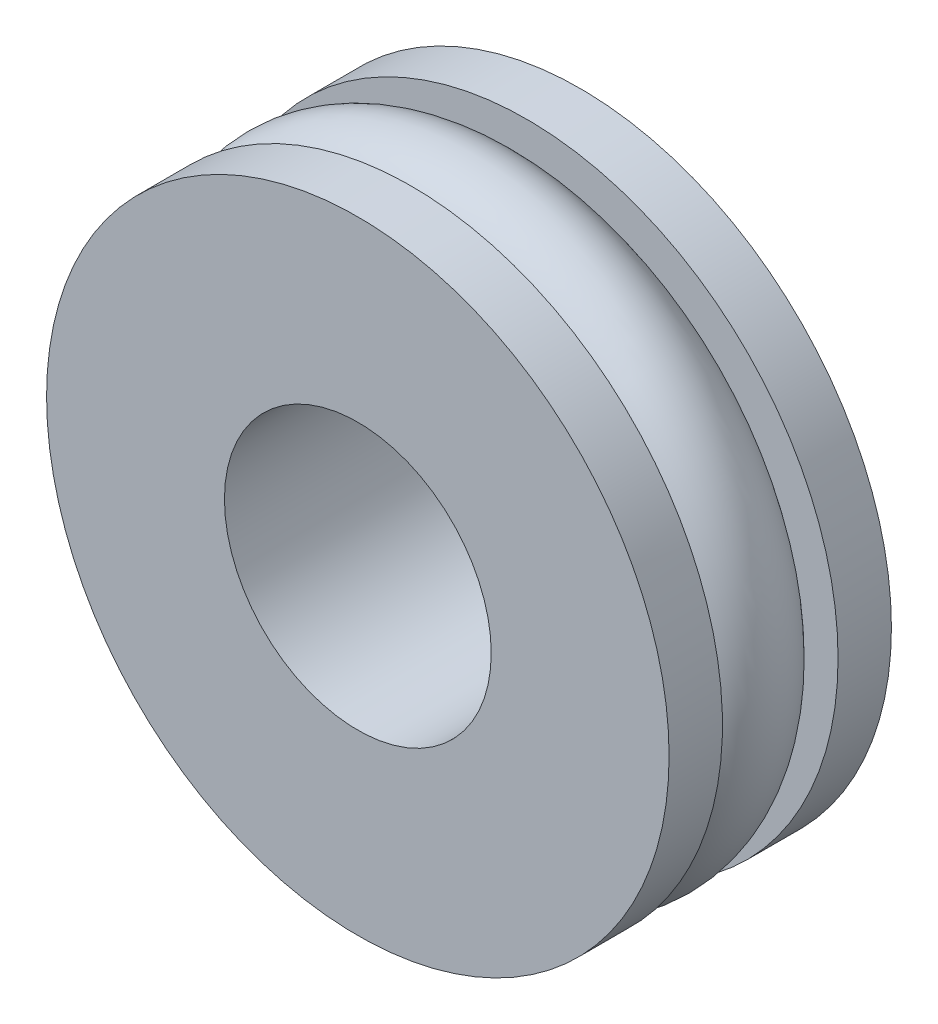
SolidWorks part; units mm, degrees
ref_plane "前视基准面" through (0, 0, 0) normal (0, 0, 1) x (1, 0, 0)
ref_plane "上视基准面" through (0, 0, 0) normal (0, 1, 0) x (1, 0, 0)
ref_plane "右视基准面" through (0, 0, 0) normal (1, 0, 0) x (0, 0, -1)
sketch "草图1" plane through (0, 0, 0) normal (0, 0, 1) x (1, 0, 0)
  circle A0 centre (0, 0) radius 3
  circle A1 centre (0, 0) radius 7
  dimension "D1" = 6
  dimension "D2" = 14
extrude "凸台-拉伸1" add sketch "草图1" along normal blind 5
sketch "草图2" plane through (0, 0, 0) normal (0, 1, 0) x (1, 0, 0)
  line L0 (7, -2.5) -> (7, -1.2) construction
  line L1 (7, -5) -> (7, 0) construction
  line L2 (7, -1.2) -> (5.7, -1.2) construction
  line L3 (5.7, -1.2) -> (7.9097, -1.2)
  line L4 (7.9097, -1.2) -> (7.9097, -3.8)
  line L5 (7.9097, -3.8) -> (5.7, -3.8)
  line L6 (0, 0) -> (0, 2.9385) construction
  arc A0 (5.7, -3.8) -> (5.7, -1.2) centre (5.7, -2.5) ccw
  dimension "D1" = 1.3
  dimension "D2" = 1.3
revolve "切除-旋转1" cut sketch "草图2" angle 360 about L6
